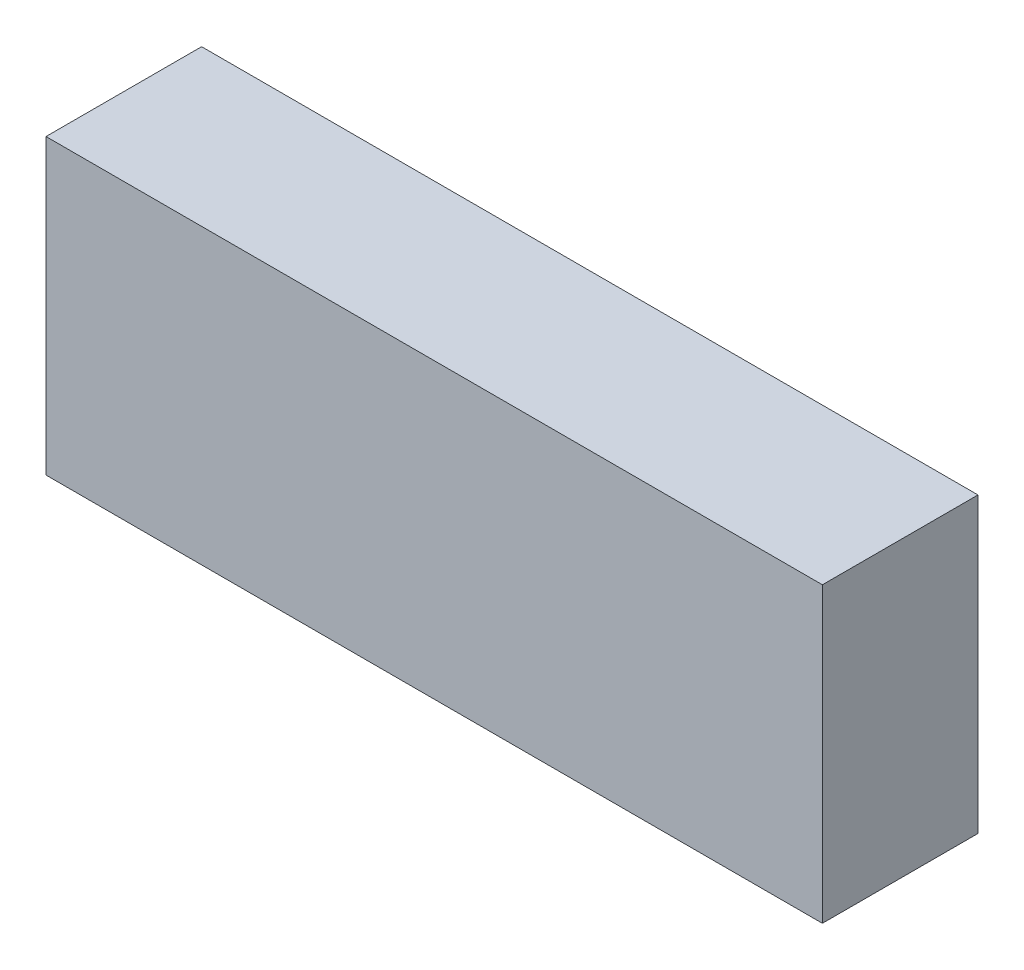
SolidWorks part; units mm, degrees
ref_plane "Front Plane" through (0, 0, 0) normal (0, 0, 1) x (1, 0, 0)
ref_plane "Top Plane" through (0, 0, 0) normal (0, 1, 0) x (1, 0, 0)
ref_plane "Right Plane" through (0, 0, 0) normal (1, 0, 0) x (0, 0, -1)
sketch "Sketch1" plane through (0, 0, 0) normal (0, 0, 1) x (1, 0, 0)
  line L1 (0, 0) -> (47.4, 0)
  line L2 (0, 0) -> (0, 17.9)
  line L3 (0, 17.9) -> (47.4, 17.9)
  line L4 (47.4, 0) -> (47.4, 17.9)
  dimension "D1" = 17.9
  dimension "D2" = 47.4
extrude "Boss-Extrude1" add sketch "Sketch1" along normal blind 9.5
